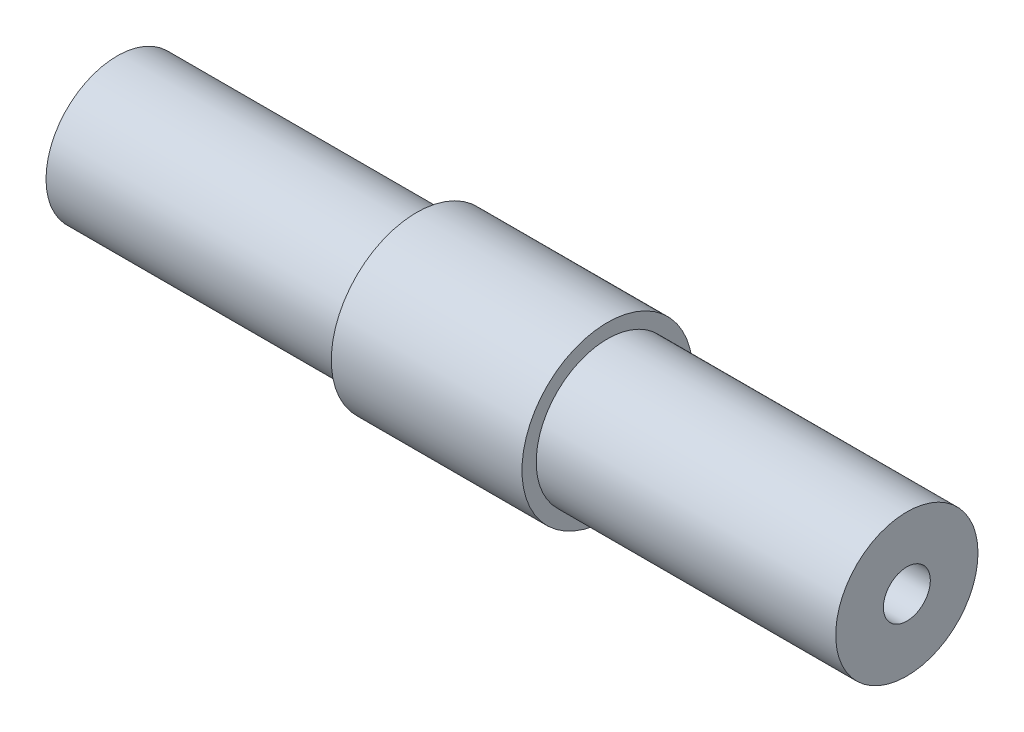
SolidWorks part; units mm, degrees
material "5052-H34"
ref_plane "正面" through (0, 0, 0) normal (0, 0, 1) x (1, 0, 0)
ref_plane "平面" through (0, 0, 0) normal (0, 1, 0) x (1, 0, 0)
ref_plane "右側面" through (0, 0, 0) normal (1, 0, 0) x (0, 0, -1)
sketch "ｽｹｯﾁ1" plane through (0, 0, 0) normal (1, 0, 0) x (0, 0, -1)
  circle A0 centre (0, 0) radius 6
  dimension "D1" = 12
extrude "ﾎﾞｽ - 押し出し1" add sketch "ｽｹｯﾁ1" along normal blind 13.4
sketch "ｽｹｯﾁ2" plane through (13.4, 0, 0) normal (1, 0, 0) x (0, 0, -1)
  circle A0 centre (0, 0) radius 5
  dimension "D1" = 10
extrude "ﾎﾞｽ - 押し出し2" add sketch "ｽｹｯﾁ2" along normal blind 21.05
sketch "ｽｹｯﾁ3" plane through (0, 0, 0) normal (-1, 0, 0) x (0, 0, 1)
  circle A0 centre (0, 0) radius 5
  dimension "D1" = 10
extrude "ﾎﾞｽ - 押し出し3" add sketch "ｽｹｯﾁ3" along normal blind 21.05
sketch "ｽｹｯﾁ4" plane through (34.45, 0, 0) normal (1, 0, 0) x (0, 0, -1)
  circle A0 centre (0, 0) radius 1.65
  dimension "D1" = 3.3
extrude "ｶｯﾄ - 押し出し1" cut sketch "ｽｹｯﾁ4" against normal blind 10
sketch "ｽｹｯﾁ5" plane through (-21.05, 0, 0) normal (-1, 0, 0) x (0, 0, 1)
  circle A0 centre (0, 0) radius 1.65
  dimension "D1" = 3.3
extrude "ｶｯﾄ - 押し出し2" cut sketch "ｽｹｯﾁ5" against normal blind 10
